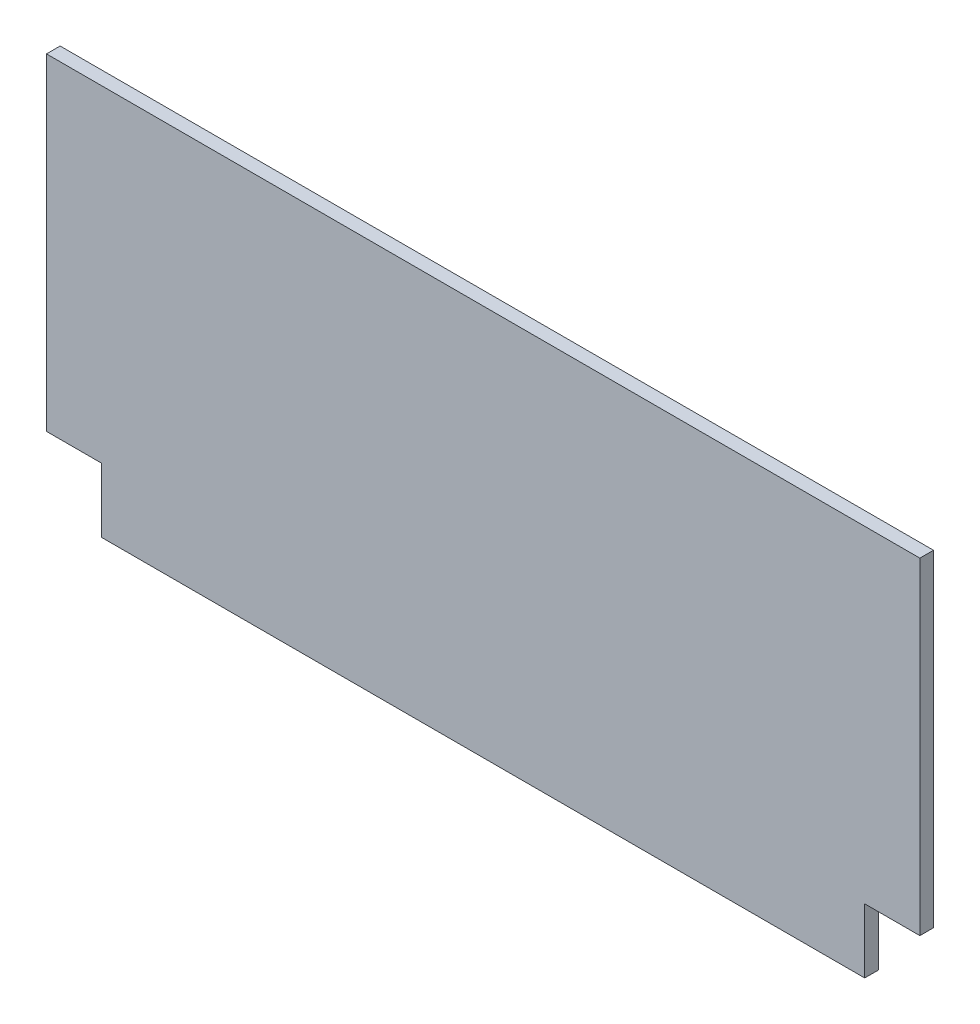
SolidWorks part; units mm, degrees
ref_plane "Front Plane" through (0, 0, 0) normal (0, 0, 1) x (1, 0, 0)
ref_plane "Top Plane" through (0, 0, 0) normal (0, 1, 0) x (1, 0, 0)
ref_plane "Right Plane" through (0, 0, 0) normal (1, 0, 0) x (0, 0, -1)
sketch "Sketch1" plane through (0, 0, 0) normal (0, 0, 1) x (1, 0, 0)
  line L0 (0, 419.1) -> (0, -127) construction
  line L1 (-609.6, 419.1) -> (609.6, 419.1)
  line L2 (-609.6, 419.1) -> (-609.6, -127)
  line L3 (-609.6, -127) -> (609.6, -127)
  line L4 (609.6, 419.1) -> (609.6, -127)
  line L5 (-609.6, 0) -> (609.6, 0) construction
  line L6 (495.3, 419.1) -> (-495.3, 419.1) construction
  point P9 (0, 0)
  dimension "D2" = 127
  dimension "D3" = 1219.2
extrude "Boss-Extrude1" add sketch "Sketch1" along normal blind 19.05
sketch "Sketch2" plane through (0, 0, 0) normal (0, 0, -1) x (-1, 0, 0)
  line L0 (-571.5, -38.1) -> (-533.4, -38.1) construction
  line L9 (-532.6062, -37.3063) -> (-609.6, -37.3063)
  line L10 (-532.6062, -37.3063) -> (-532.6062, -127)
  line L11 (-532.6062, -127) -> (-609.6, -127)
  line L12 (-609.6, -37.3063) -> (-609.6, -127)
  line L13 (-571.1031, -127) -> (-571.1031, -37.3063) construction
  line L14 (-532.6062, -82.1531) -> (-609.6, -82.1531) construction
  line L15 (-533.4, -38.1) -> (-533.4, -127) construction
  line L16 (533.4, -38.1) -> (571.5, -38.1) construction
  line L17 (532.6063, -37.3063) -> (609.6, -37.3063)
  line L18 (532.6063, -37.3063) -> (532.6063, -127)
  line L19 (532.6063, -127) -> (609.6, -127)
  line L20 (609.6, -37.3063) -> (609.6, -127)
  line L21 (571.1031, -127) -> (571.1031, -37.3063) construction
  line L22 (532.6063, -82.1531) -> (609.6, -82.1531) construction
  line L23 (533.4, -127) -> (533.4, -38.1) construction
  point P159 (571.1031, -82.1531)
  point P169 (-571.1031, -82.1531)
  dimension "D1" = 0.7937
  dimension "D2" = 0.7937
  dimension "D3" = 0.7938
  dimension "D4" = 0.7937
extrude "Cut-Extrude1" cut sketch "Sketch2" against normal through all
